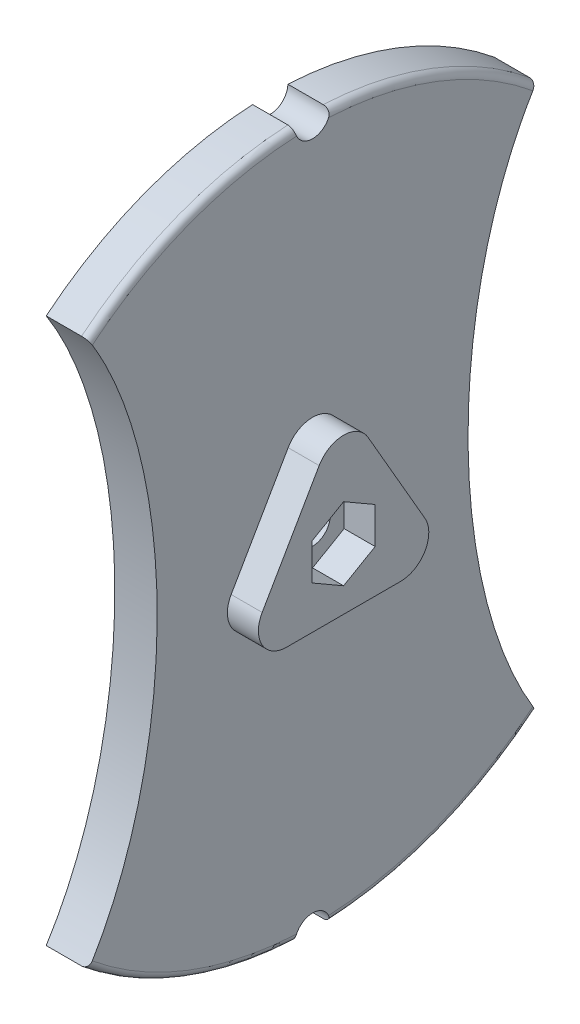
SolidWorks part; units mm, degrees
material "Custom Plastic"
ref_plane "Front Plane" through (0, 0, 0) normal (0, 0, 1) x (1, 0, 0)
ref_plane "Top Plane" through (0, 0, 0) normal (0, 1, 0) x (1, 0, 0)
ref_plane "Right Plane" through (0, 0, 0) normal (1, 0, 0) x (0, 0, -1)
sketch "Sketch2" plane through (0, 0, 0) normal (1, 0, 0) x (0, 0, -1)
  line L0 (55, 0) -> (-55, 0) construction
  arc A0 (3.1742, -63.4206) -> (3.1742, 63.4206) centre (0, 0) ccw
  circle A1 centre (0, 0) radius 3.175
  arc A2 (-3.1738, -63.4206) -> (3.1742, -63.4206) centre (0.0002, -63.5) cw
  arc A3 (-3.1738, 63.4206) -> (3.1742, 63.4206) centre (0.0002, 63.5) ccw
  arc A4 (-3.1738, 63.4206) -> (-3.1738, -63.4206) centre (0, 0) ccw
  dimension "D1" = 127
  dimension "D2" = 6.35
extrude "Boss-Extrude1" add sketch "Sketch2" along normal blind 7.62
sketch "Sketch3" plane through (7.62, 0, 0) normal (1, 0, 0) x (0, 0, -1)
  line L0 (-5.675, 3.2765) -> (-5.675, -3.2765)
  line L1 (19.05, -10.9985) -> (0, 21.997)
  line L2 (0, 21.997) -> (-19.05, -10.9985)
  line L3 (-19.05, -10.9985) -> (19.05, -10.9985)
  line L4 (5.675, -3.2765) -> (5.675, 3.2765)
  line L5 (5.675, 3.2765) -> (0, 6.5529)
  line L6 (0, 6.5529) -> (-5.675, 3.2765)
  line L7 (-5.675, -3.2765) -> (0, -6.5529)
  line L8 (0, -6.5529) -> (5.675, -3.2765)
  circle A0 centre (0, 0) radius 10.9985 construction
  circle A1 centre (0, 0) radius 5.675 construction
  dimension "D1" = 11.35
  dimension "D2" = 38.1
extrude "Boss-Extrude2" add sketch "Sketch3" along normal blind 5.58
fillet "Fillet1" radius 5.08 3 edges at (10.41, -10.9985, -19.05) (10.41, 21.997, 0) (10.41, -10.9985, 19.05)
fillet "Fillet3" radius 1.27 2 edges at (7.62, 0, -63.5) (7.62, 0, 63.5)
sketch "Sketch4" plane through (0, 0, 0) normal (-1, 0, 0) x (0, 0, 1)
  arc A1 (-3.1742, 63.4206) -> (-3.1742, -63.4206) centre (0, 0) ccw construction
  ellipse E0 centre (-63.5, 0) end of major axis (-63.5, -64.7517) minor radius 35.5352
extrude "Cut-Extrude1" cut sketch "Sketch4" against normal blind 8.89
mirror "Mirror1" about plane through (0, 0, 0) normal (0, 0, 1) of "Cut-Extrude1"
